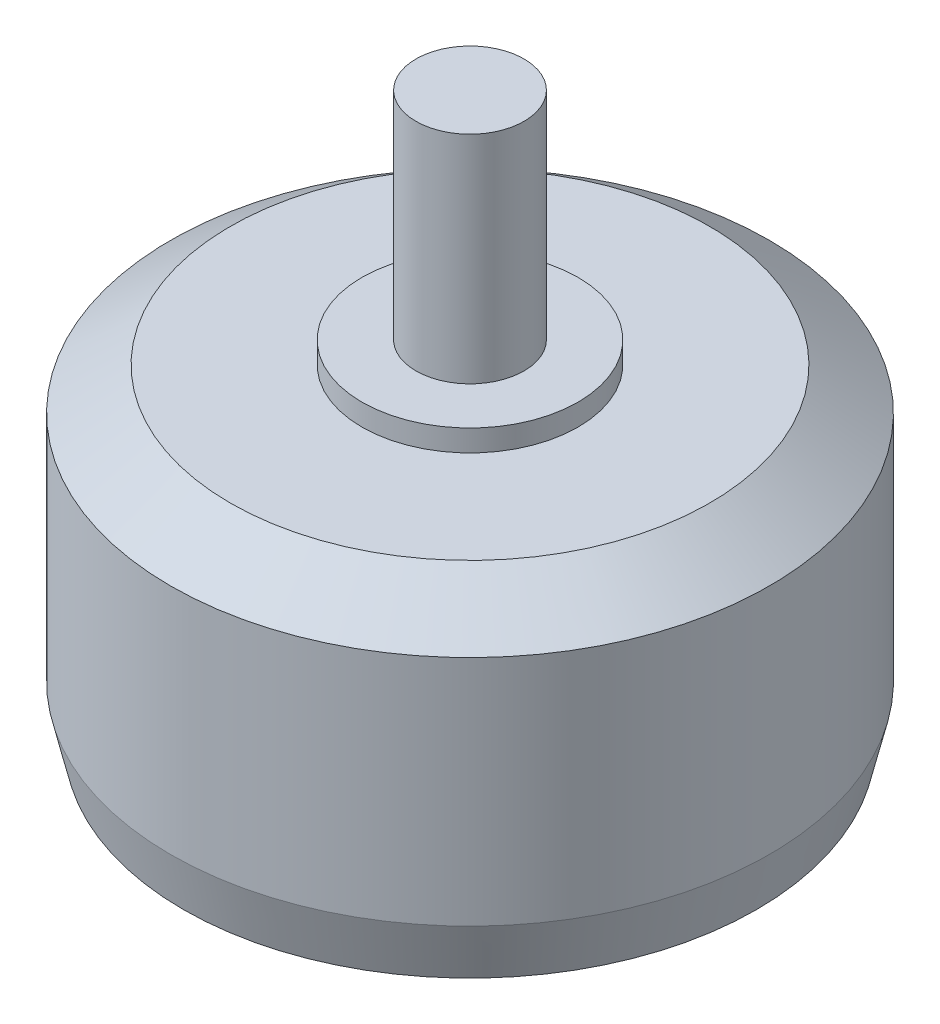
SolidWorks part; units mm, degrees
ref_plane "Front Plane" through (0, 0, 0) normal (0, 0, 1) x (1, 0, 0)
ref_plane "Top Plane" through (0, 0, 0) normal (0, 1, 0) x (1, 0, 0)
ref_plane "Right Plane" through (0, 0, 0) normal (1, 0, 0) x (0, 0, -1)
sketch "Sketch1" plane through (0, 0, 0) normal (1, 0, 0) x (0, 0, -1)
  line L0 (0, 0) -> (-13.2573, 0)
  line L1 (-13.2573, 0) -> (-13.85, 2.5035)
  line L2 (-13.85, 2.5035) -> (-13.85, 13.2611)
  line L3 (-13.85, 13.2611) -> (-11.0869, 15.2)
  line L4 (-11.0869, 15.2) -> (-5, 15.2)
  line L5 (-5, 15.2) -> (-5, 16.2)
  line L6 (-5, 16.2) -> (-2.5, 16.2)
  line L7 (-2.5, 16.2) -> (-2.5, 26.2)
  line L8 (-2.5, 26.2) -> (0, 26.2)
  line L9 (0, 26.2) -> (0, 0)
  dimension "D1" = 2.5
  dimension "D2" = 11
  dimension "D3" = 13.85
  dimension "D4" = 15.2
  dimension "D5" = 2.5
  dimension "D6" = 1
revolve "Revolve1" add sketch "Sketch1" angle 360 about L9
sketch "Sketch2" plane through (0, 0, 0) normal (0, -1, 0) x (1, 0, 0)
  line L0 (-8, 0) -> (8, 0) construction
  line L1 (0, 6) -> (0, -6) construction
  circle A0 centre (0, 6) radius 1
  circle A1 centre (8, 0) radius 1
  circle A2 centre (0, -6) radius 1
  circle A3 centre (-8, 0) radius 1
  dimension "D1" = 16
  dimension "D3" = 2
  dimension "D2" = 12
extrude "Cut-Extrude1" cut sketch "Sketch2" against normal blind 10.16
